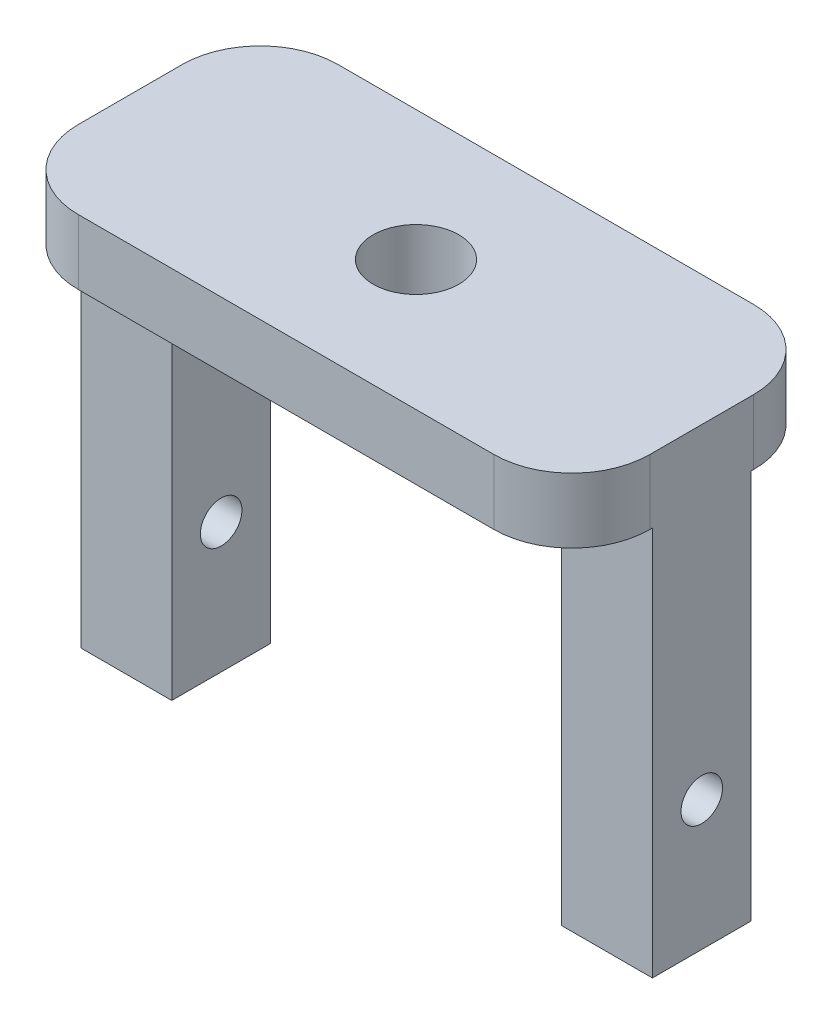
SolidWorks part; units mm, degrees
ref_plane "前视基准面" through (0, 0, 0) normal (0, 0, 1) x (1, 0, 0)
ref_plane "上视基准面" through (0, 0, 0) normal (0, 1, 0) x (1, 0, 0)
ref_plane "右视基准面" through (0, 0, 0) normal (1, 0, 0) x (0, 0, -1)
sketch "草图1" plane through (0, 0, 0) normal (0, 1, 0) x (1, 0, 0)
  line L1 (-22, -10) -> (22, -10)
  line L2 (-22, -10) -> (-22, 10)
  line L3 (-22, 10) -> (22, 10)
  line L4 (22, -10) -> (22, 10)
  line L5 (-22, -10) -> (22, 10) construction
  line L6 (-22, 10) -> (22, -10) construction
  point P0 (0, 0)
extrude "凸台-拉伸1" add sketch "草图1" against normal blind 5
sketch "草图2" plane through (0, -5, 0) normal (0, -1, 0) x (1, 0, 0)
  line L0 (-22, -10) -> (-22, 10) construction
  line L1 (-22, 3.8) -> (-15, 3.8)
  line L2 (-22, 3.8) -> (-22, -3.8)
  line L3 (-22, -3.8) -> (-15, -3.8)
  line L4 (-15, 3.8) -> (-15, -3.8)
  line L5 (22, 10) -> (22, -10) construction
  line L7 (22, 3.8) -> (15, 3.8)
  line L8 (22, 3.8) -> (22, -3.8)
  line L9 (22, -3.8) -> (15, -3.8)
  line L10 (15, 3.8) -> (15, -3.8)
  point P12 (-48.332, 18.6224)
  point P13 (0, 0)
  point P14 (0, 0)
extrude "凸台-拉伸2" add sketch "草图2" along normal blind 30
sketch "草图3" plane through (0, -5, 0) normal (0, -1, 0) x (1, 0, 0)
  circle A0 centre (0, 0) radius 3.3
extrude "切除-拉伸1" cut sketch "草图3" against normal through all
fillet "圆角1" radius 6 4 edges at (22, -2.5, 10) (22, -2.5, -10) (-22, -2.5, 10) (-22, -2.5, -10)
sketch "草图4" plane through (22, 0, 0) normal (1, 0, 0) x (0, 0, -1)
  circle A0 centre (0, -25) radius 1.6
extrude "切除-拉伸2" cut sketch "草图4" against normal through all
